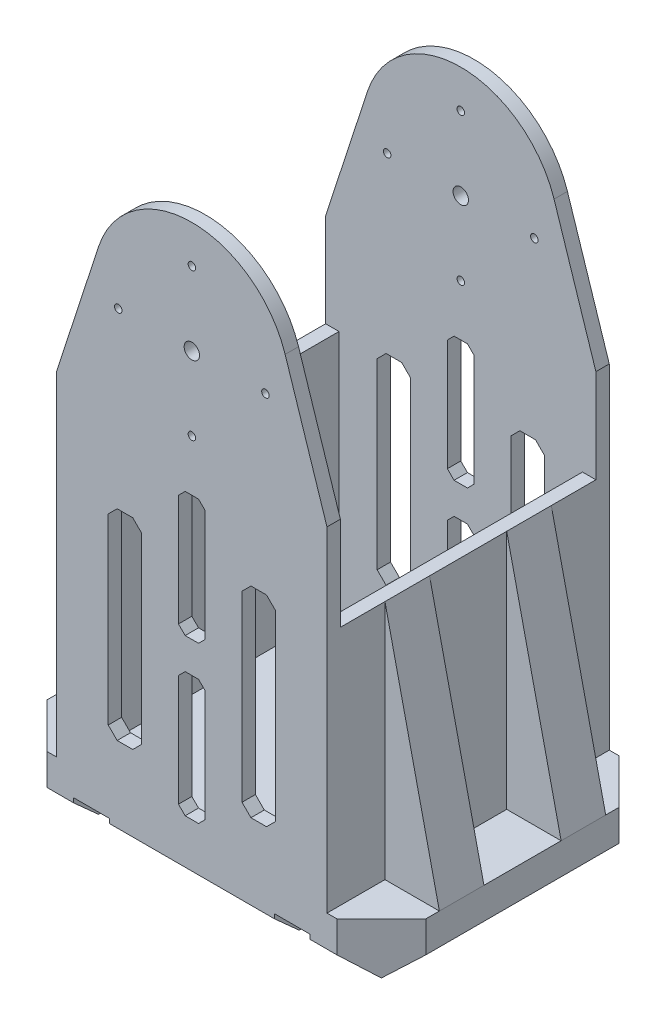
SolidWorks part; units mm, degrees
ref_plane "前视基准面" through (0, 0, 0) normal (0, 0, 1) x (1, 0, 0)
ref_plane "上视基准面" through (0, 0, 0) normal (0, 1, 0) x (1, 0, 0)
ref_plane "右视基准面" through (0, 0, 0) normal (1, 0, 0) x (0, 0, -1)
sketch "草图1" plane through (0, 0, 0) normal (0, 1, 0) x (1, 0, 0)
  line L0 (-27.3, 28.65) -> (27.3, 28.65)
  line L1 (-30.3, 31.65) -> (30.3, 31.65)
  line L2 (-30.3, 31.65) -> (-30.3, -31.65)
  line L3 (-30.3, -31.65) -> (30.3, -31.65)
  line L4 (30.3, 31.65) -> (30.3, -31.65)
  line L9 (27.3, 28.65) -> (27.3, -28.65)
  line L10 (-27.3, -28.65) -> (27.3, -28.65)
  line L11 (-27.3, 28.65) -> (-27.3, -28.65)
  line L12 (0, -28.65) -> (0, 28.65) construction
  line L13 (-27.3, 0) -> (27.3, 0) construction
  point P12 (0, 0)
  dimension "D1" = 3
  dimension "D2" = 63.3
  dimension "D6" = 60.6
extrude "凸台-拉伸1" add sketch "草图1" along normal blind 60
sketch "草图2" plane through (0, 60, 0) normal (0, 1, 0) x (1, 0, 0)
  line L1 (30.3, -31.65) -> (30.3, 31.65) construction
  line L2 (-30.3, 31.65) -> (30.3, 31.65)
  line L3 (-30.3, 31.65) -> (-30.3, 28.65)
  line L4 (-30.3, 28.65) -> (30.3, 28.65)
  line L5 (30.3, 31.65) -> (30.3, 28.65)
  line L7 (-30.3, -31.65) -> (30.3, -31.65)
  line L8 (-30.3, -31.65) -> (-30.3, -28.65)
  line L9 (-30.3, -28.65) -> (30.3, -28.65)
  line L10 (30.3, -31.65) -> (30.3, -28.65)
  dimension "D1" = 3
  dimension "D2" = 3
extrude "凸台-拉伸2" add sketch "草图2" along normal blind 65
sketch "草图3" plane through (0, 0, -31.65) normal (0, 0, -1) x (-1, 0, 0)
  line L0 (-30.3, 103) -> (30.3, 103) construction
  line L1 (-30.3, 125) -> (-30.3, 0) construction
  line L2 (30.3, 125) -> (30.3, 0) construction
  line L3 (-30.3, 125) -> (30.3, 125) construction
  line L4 (30.3, 81) -> (-30.3, 81) construction
  line L5 (-30.3, 81) -> (-20.9191, 109.8112)
  line L6 (30.3, 81) -> (20.9191, 109.8112)
  line L7 (-30.3, 81) -> (-30.3, 125)
  line L8 (-30.3, 125) -> (30.3, 183)
  line L9 (30.3, 183) -> (30.3, 81)
  circle A1 centre (0, 103) radius 22 construction
  arc A2 (-20.9191, 109.8112) -> (20.9191, 109.8112) centre (0, 103) cw
  point P13 (0, 81)
  line M4 (30.3, 0) -> (30.3, 125)
  line M5 (30.3, 125) -> (-30.3, 125)
  line M6 (-30.3, 125) -> (-30.3, 0)
  dimension "D1" = 44
  dimension "D2" = 22
extrude "切除-拉伸1" cut sketch "草图3" against normal blind 65 contours A2 L6 M5 M4 | L5 A2 L8 M6
sketch "草图8" plane through (0, 0, 31.65) normal (0, 0, 1) x (1, 0, 0)
  line L0 (-16.5, 100) -> (16.5, 100) construction
  line L1 (0, 83.5) -> (0, 116.5) construction
  arc A0 (-20.9191, 109.8112) -> (20.9191, 109.8112) centre (0, 100) cw construction
  circle A1 centre (0, 100) radius 16.5 construction
  circle A2 centre (0, 116.5) radius 0.84
  circle A3 centre (16.5, 100) radius 0.84
  circle A4 centre (0, 83.5) radius 0.84
  circle A5 centre (-16.5, 100) radius 0.84
  arc A6 (20.9191, 109.8112) -> (-20.9191, 109.8112) centre (0, 103) ccw construction
  point P9 (0, 100)
  point P12 (0, 100)
  dimension "D1" = 33
  dimension "D2" = 1.68
  dimension "D3" = 1.68
  dimension "D4" = 1.68
  dimension "D5" = 1.68
  dimension "D6" = 3
sketch "草图9" plane through (0, 0, -31.65) normal (0, 0, -1) x (-1, 0, 0)
  arc A0 (-20.9191, 109.8112) -> (20.9191, 109.8112) centre (0, 100) cw construction
  circle A1 centre (0, 100) radius 1.725
  dimension "D1" = 3.45
  dimension "D2" = 19
extrude "切除-拉伸4" cut sketch "草图9" against normal blind 80
ref_plane "基准面1" through (0, 0, 56.95) normal (0, 0, 1) x (1, 0, 0)
sketch "草图10" plane through (0, 0, 0) normal (0, -1, 0) x (1, 0, 0)
  line L0 (20.9191, 31.65) -> (-20.9191, 31.65) construction
  line L5 (-27.3, -28.65) -> (27.3, 28.65) construction
  line L6 (41.5527, 0) -> (-41.5527, 0) construction
  line L7 (-42.5, -31.65) -> (42.5, -31.65)
  line L8 (-42.5, -31.65) -> (-42.5, 31.65)
  line L9 (-42.5, 31.65) -> (42.5, 31.65)
  line L10 (42.5, -31.65) -> (42.5, 31.65)
  line L11 (-42.5, -31.65) -> (42.5, 31.65) construction
  line L12 (-42.5, 31.65) -> (42.5, -31.65) construction
  point P0 (0, 0)
  point P7 (0, 0)
  dimension "D1" = 85
extrude "凸台-拉伸3" add sketch "草图10" along normal mid plane 12
chamfer "倒角1" distance 10 angle 45 4 edges at (42.5, 0, -31.65) (42.5, 0, 31.65) (-42.5, 0, 31.65) (-42.5, 0, -31.65)
chamfer "倒角2" distance 5 angle 48 4 edges at (42.5, -6, 0) (-42.5, -6, 0) (0, -6, -31.65) (0, -6, 31.65)
sketch "草图12" plane through (0, 0, -31.65) normal (0, 0, -1) x (-1, 0, 0)
  line L0 (36.9469, -6) -> (-36.9469, -6) construction
  line L1 (-26.5, -6) -> (-18.5, -6)
  line L2 (-26.5, -6) -> (-26.5, 0)
  line L3 (-26.5, 0) -> (-18.5, 0)
  line L4 (-18.5, -6) -> (-18.5, 0)
  line L5 (-42.5, -1) -> (-42.5, 6) construction
  line L6 (0, 34.815) -> (0, -34.815) construction
  line L7 (18.5, -6) -> (18.5, 0)
  line L8 (26.5, 0) -> (18.5, 0)
  line L9 (26.5, -6) -> (26.5, 0)
  line L10 (26.5, -6) -> (18.5, -6)
  dimension "D1" = 8
  dimension "D2" = 6
  dimension "D3" = 16
extrude "切除-拉伸5" cut sketch "草图12" against normal blind 80
sketch "草图13" plane through (0, -6, 0) normal (0, -1, 0) x (1, 0, 0)
  line L5 (18.5, 26.0969) -> (18.5, -26.0969) construction
  line L6 (-18.5, 6) -> (18.5, 6)
  line L7 (-18.5, 6) -> (-18.5, 16)
  line L8 (-18.5, 16) -> (18.5, 16)
  line L9 (18.5, 6) -> (18.5, 16)
  line L10 (-18.5, 6) -> (18.5, 16) construction
  line L11 (-18.5, 16) -> (18.5, 6) construction
  line L12 (33.33, 0) -> (-33.33, 0) construction
  line L13 (-18.5, -16) -> (18.5, -6) construction
  line L14 (-18.5, -6) -> (18.5, -16) construction
  line L15 (18.5, -6) -> (18.5, -16)
  line L16 (-18.5, -16) -> (18.5, -16)
  line L17 (-18.5, -6) -> (-18.5, -16)
  line L18 (-18.5, -6) -> (18.5, -6)
  point P0 (0, 11)
  point P15 (0, -11)
  dimension "D1" = 6
  dimension "D2" = 10
extrude "切除-拉伸7" cut sketch "草图13" against normal blind 6
sketch "草图14" plane through (0, -6, 0) normal (0, -1, 0) x (1, 0, 0)
  line L1 (-18.5, -6) -> (18.5, -6)
  line L2 (-18.5, -6) -> (-18.5, 6)
  line L3 (-18.5, 6) -> (18.5, 6)
  line L4 (18.5, -6) -> (18.5, 6)
  line L5 (-18.5, -6) -> (18.5, 6) construction
  line L6 (-18.5, 6) -> (18.5, -6) construction
  point P0 (0, 0)
extrude "切除-拉伸8" cut sketch "草图14" against normal blind 0.3
sketch "草图15" plane through (0, 6, 0) normal (0, 1, 0) x (1, 0, 0)
  line L0 (-30.3, 28.65) -> (-30.3, -28.65) construction
  line L1 (-30.3, 8) -> (-42.5, 8)
  line L2 (-30.3, 8) -> (-30.3, 18)
  line L3 (-30.3, 18) -> (-42.5, 18)
  line L4 (-42.5, 8) -> (-42.5, 18)
  line L5 (-42.5, -21.65) -> (-42.5, 21.65) construction
  dimension "D1" = 10
  dimension "D2" = 8
sketch "草图16" plane through (0, 60, 0) normal (0, 1, 0) x (1, 0, 0)
  line L0 (-30.3, 18) -> (-30.3, 8)
  line L1 (-30.3, 18) -> (-27.3, 18)
  line L2 (-27.3, 28.65) -> (-27.3, -28.65) construction
  line L3 (-27.3, 18) -> (-27.3, 8)
  line L4 (-27.3, 28.65) -> (-27.3, -28.65) construction
  line L5 (-27.3, 8) -> (-30.3, 8)
ref_plane "基准面3" through (0, 0, -13.65) normal (0, 0, -1) x (-1, 0, 0)
sketch "草图18" plane through (0, 0, -13.65) normal (0, 0, -1) x (-1, 0, 0)
  line L0 (30.3, 60) -> (42.5, 6)
  line L1 (42.5, 6) -> (30.3, 6)
  line L2 (30.3, 6) -> (30.3, 60)
extrude "凸台-拉伸4" add sketch "草图18" along normal mid plane 10
mirror "镜向1" about plane through (0, 0, 0) normal (0, 0, 1) of "凸台-拉伸4"
mirror "镜向2" about plane through (0, 0, 0) normal (1, 0, 0) of "镜向1", "凸台-拉伸4"
extrude "切除-拉伸9" cut sketch "草图8" against normal blind 80
sketch "草图19" plane through (0, 0, -31.65) normal (0, 0, -1) x (-1, 0, 0)
  line L1 (-1.5, 44) -> (1.5, 44)
  line L2 (-3, 45.5) -> (-3, 70.5)
  line L3 (-1.5, 72) -> (1.5, 72)
  line L4 (3, 45.5) -> (3, 70.5)
  line L5 (-3, 44) -> (3, 72) construction
  line L6 (-3, 72) -> (3, 44) construction
  line L11 (-16.75, 61) -> (-13.25, 61)
  line L12 (-18.75, 59) -> (-18.75, 18)
  line L13 (-16.75, 16) -> (-13.25, 16)
  line L14 (-11.25, 59) -> (-11.25, 18)
  line L15 (-18.75, 61) -> (-11.25, 16) construction
  line L16 (-18.75, 16) -> (-11.25, 61) construction
  line L21 (-3, 70.5) -> (-1.5, 72)
  line L22 (1.5, 72) -> (3, 70.5)
  line L23 (-3, 45.5) -> (-1.5, 44)
  line L24 (1.5, 44) -> (3, 45.5)
  line L25 (-3, 10.5) -> (-3, 35.5)
  line L26 (-3, 35.5) -> (-1.5, 37)
  line L27 (-1.5, 37) -> (1.5, 37)
  line L28 (1.5, 37) -> (3, 35.5)
  line L29 (3, 10.5) -> (3, 35.5)
  line L30 (-3, 10.5) -> (-1.5, 9)
  line L31 (-1.5, 9) -> (1.5, 9)
  line L32 (1.5, 9) -> (3, 10.5)
  line L33 (-18.75, 59) -> (-16.75, 61)
  line L34 (-13.25, 61) -> (-11.25, 59)
  line L35 (-18.75, 18) -> (-16.75, 16)
  line L36 (-13.25, 16) -> (-11.25, 18)
  line L37 (0, 34.815) -> (0, -34.815) construction
  line L38 (18.75, 16) -> (11.25, 61) construction
  line L39 (18.75, 61) -> (11.25, 16) construction
  line L40 (13.25, 16) -> (11.25, 18)
  line L41 (18.75, 18) -> (16.75, 16)
  line L42 (13.25, 61) -> (11.25, 59)
  line L43 (18.75, 59) -> (16.75, 61)
  line L44 (11.25, 59) -> (11.25, 18)
  line L45 (16.75, 16) -> (13.25, 16)
  line L46 (18.75, 59) -> (18.75, 18)
  line L47 (16.75, 61) -> (13.25, 61)
  point P0 (0, 58)
  point P5 (-15, 38.5)
  point P49 (15, 38.5)
  dimension "D1" = 2
  dimension "D3" = 58
  dimension "D5" = 15
  dimension "D6" = 5.5
  dimension "D7" = 7.5
  dimension "D8" = 45
extrude "切除-拉伸10" cut sketch "草图19" against normal blind 80
